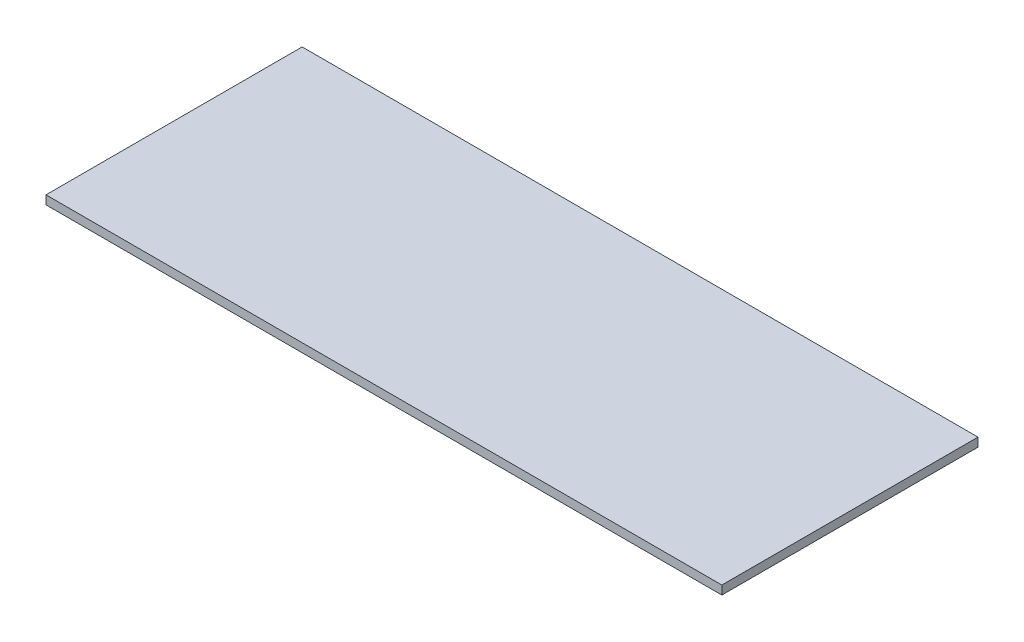
SolidWorks part; units mm, degrees
ref_plane "Front Plane" through (0, 0, 0) normal (0, 0, 1) x (1, 0, 0)
ref_plane "Top Plane" through (0, 0, 0) normal (0, 1, 0) x (1, 0, 0)
ref_plane "Right Plane" through (0, 0, 0) normal (1, 0, 0) x (0, 0, -1)
ref_plane "Plane_PCB" through (0, 5.6, 0) normal (0, 1, 0) x (1, 0, 0)
sketch "Sk_PCB" plane through (0, 5.6, 0) normal (0, 1, 0) x (1, 0, 0)
  line L1 (4.4, 4.4) -> (128.4, 4.4)
  line L2 (4.4, 4.4) -> (4.4, 51.4)
  line L3 (4.4, 51.4) -> (128.4, 51.4)
  line L4 (128.4, 4.4) -> (128.4, 51.4)
extrude "Perfboard 124x47x1.6" add sketch "Sk_PCB" along normal blind 1.6
